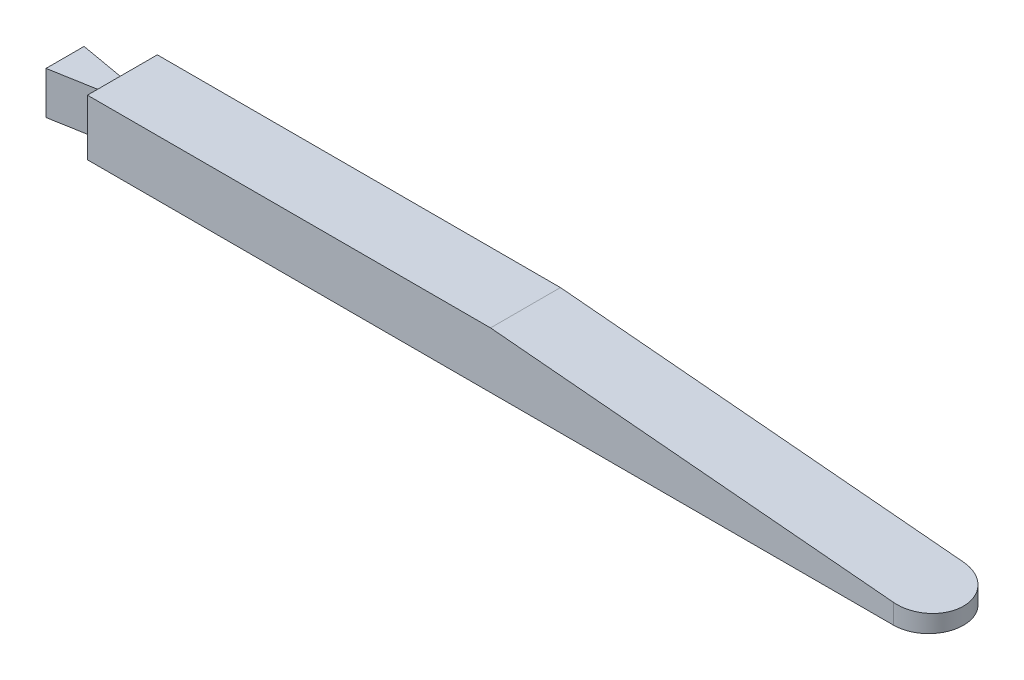
SolidWorks part; units mm, degrees
ref_plane "Front Plane" through (0, 0, 0) normal (0, 0, 1) x (1, 0, 0)
ref_plane "Top Plane" through (0, 0, 0) normal (0, 1, 0) x (1, 0, 0)
ref_plane "Right Plane" through (0, 0, 0) normal (1, 0, 0) x (0, 0, -1)
sketch "Sketch2" plane through (0, 0, 0) normal (0, 1, 0) x (1, 0, 0)
  line L29 (-18.2118, -9.9149) -> (-18.2118, -31.5049)
  line L30 (-18.2118, -9.9149) -> (14.3002, -15.6476)
  line L31 (-18.2118, -31.5049) -> (14.3002, -25.7721)
  line L32 (14.3002, -0.8979) -> (471.5002, -0.8979)
  line L33 (14.3002, -40.5219) -> (471.5002, -40.5219)
  line L35 (14.3002, -0.8979) -> (14.3002, -15.6476)
  line L36 (14.3002, -40.5219) -> (14.3002, -25.7721)
  arc A3 (471.5002, -40.5219) -> (471.5002, -0.8979) centre (471.5002, -20.7099) ccw
  dimension "D4" = 80
  dimension "D5" = 39.624
  dimension "D8" = 39.624
  dimension "D3" = 80
  dimension "D2" = 21.59
  dimension "D6" = 457.2
  dimension "D7" = 457.2
  dimension "D9" = 14.7497
  dimension "D10" = 14.7497
  dimension "D11" = 18.2118
  dimension "D12" = 15.6476
  dimension "D13" = 40.5219
extrude "Boss-Extrude1" add sketch "Sketch2" along normal blind 31.75
sketch "Sketch3" plane through (0, 31.75, 0) normal (0, 1, 0) x (1, 0, 0)
  line L0 (-18.2118, -9.9149) -> (-18.2118, -31.5049)
  line L1 (-18.2118, -31.5049) -> (14.3002, -25.7721)
  line L2 (14.3002, -25.7721) -> (14.3002, -15.6476)
  line L3 (14.3002, -15.6476) -> (-18.2118, -9.9149)
extrude "Cut-Extrude1" cut sketch "Sketch3" against normal blind 7.62
sketch "Sketch5" plane through (0, 0, 40.5219) normal (0, 0, 1) x (1, 0, 0)
  line L0 (242.9002, 31.75) -> (491.3122, 9.4252)
  line L1 (14.3002, 31.75) -> (471.5002, 31.75) construction
  line L2 (491.3122, 0) -> (491.3122, 31.75) construction
  line L3 (491.3122, 9.4252) -> (491.3122, 31.75)
  line L4 (491.3122, 31.75) -> (242.9002, 31.75)
  dimension "D1" = 5.135
extrude "Cut-Extrude4" cut sketch "Sketch5" against normal blind 39.624
